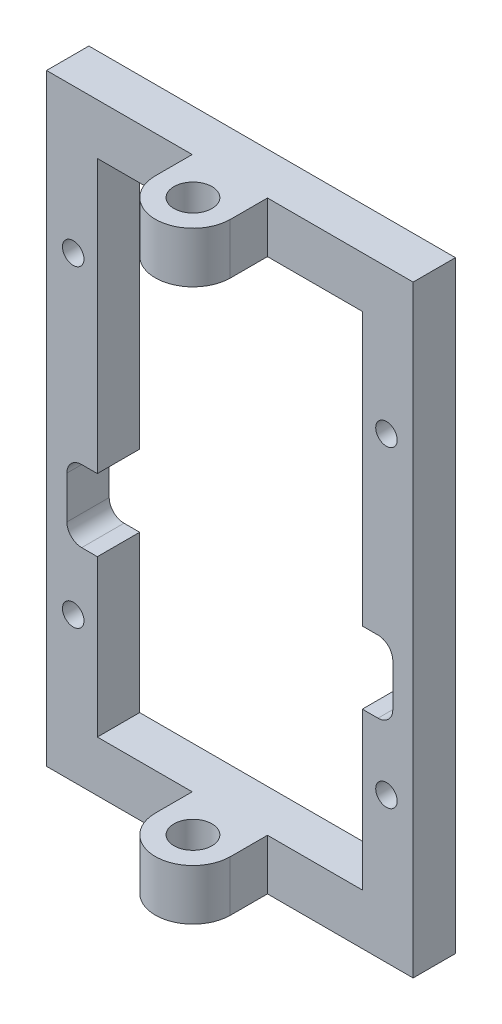
SolidWorks part; units mm, degrees
ref_plane "Front Plane" through (0, 0, 0) normal (0, 0, 1) x (1, 0, 0)
ref_plane "Top Plane" through (0, 0, 0) normal (0, 1, 0) x (1, 0, 0)
ref_plane "Right Plane" through (0, 0, 0) normal (1, 0, 0) x (0, 0, -1)
sketch "Sketch2" plane through (0, 0, 0) normal (0, 0, 1) x (1, 0, 0)
  line L1 (-21.65, 35.595) -> (21.65, 35.595)
  line L2 (-21.65, 35.595) -> (-21.65, -35.595)
  line L3 (-21.65, -35.595) -> (21.65, -35.595)
  line L4 (21.65, 35.595) -> (21.65, -35.595)
  line L5 (-15.65, 29.595) -> (15.65, 29.595)
  line L6 (-15.65, 29.595) -> (-15.65, -29.595)
  line L7 (-15.65, -29.595) -> (15.65, -29.595)
  line L8 (15.65, 29.595) -> (15.65, -29.595)
  dimension "D1" = 71.19
  dimension "D2" = 43.3
  dimension "D3" = 35.595
  dimension "D4" = 21.65
  dimension "D5" = 6
  dimension "D6" = 6
  dimension "D7" = 6
  dimension "D8" = 6
extrude "Boss-Extrude1" add sketch "Sketch2" along normal blind 5
sketch "Sketch3" plane through (0, 0, 5) normal (0, 0, 1) x (1, 0, 0)
  line L0 (0, 35.595) -> (0, -35.595)
  line L1 (21.65, 35.595) -> (-21.65, 35.595) construction
  line L2 (-21.65, -35.595) -> (21.65, -35.595) construction
  line L3 (15.65, 29.595) -> (-15.65, 29.595) construction
  line L4 (-4.445, 35.595) -> (4.445, 35.595)
  line L5 (-4.445, 35.595) -> (-4.445, 29.595)
  line L6 (-4.445, 29.595) -> (4.445, 29.595)
  line L7 (4.445, 35.595) -> (4.445, 29.595)
  line L8 (-15.65, -29.595) -> (15.65, -29.595) construction
  line L9 (-4.445, -29.595) -> (4.445, -29.595)
  line L10 (-4.445, -29.595) -> (-4.445, -35.595)
  line L11 (-4.445, -35.595) -> (4.445, -35.595)
  line L12 (4.445, -29.595) -> (4.445, -35.595)
  point P18 (4.445, -32.595)
  dimension "D1" = 8.89
  dimension "D2" = 4.445
  dimension "D3" = 8.89
extrude "Boss-Extrude2" add sketch "Sketch3" along normal blind 8.8 contours L4 L7 L6 L5 | L9 L12 L11 L10
sketch "Sketch5" plane through (0, 35.595, 0) normal (0, 1, 0) x (1, 0, 0)
  line L0 (4.445, -13.8) -> (4.445, -5) construction
  line L1 (-4.445, -13.8) -> (-4.445, -5) construction
  arc A0 (4.445, -9.4) -> (-4.445, -9.4) centre (0, -9.3548) cw
  circle A1 centre (0, -9.3548) radius 2.2479
  line M5 (-4.445, -5) -> (-4.445, -13.8)
  line M6 (-4.445, -13.8) -> (4.445, -13.8)
  line M7 (4.445, -13.8) -> (4.445, -5)
extrude "Cut-Extrude1" cut sketch "Sketch5" against normal through all and the other way through all contours A0 M6 M5 | A0 M7 M6 | A1
sketch "Sketch6" plane through (0, 0, 0) normal (0, 0, -1) x (-1, 0, 0)
  line L0 (-21.65, 35.595) -> (21.65, 35.595) construction
  line L1 (-21.65, -35.595) -> (-21.65, 35.595) construction
  line L2 (21.65, 35.595) -> (21.65, -35.595) construction
  line L3 (21.65, -35.595) -> (-21.65, -35.595) construction
  line L4 (-17.5, -2.5899) -> (-15.65, -2.5899)
  line L5 (-15.65, -29.595) -> (-15.65, 29.595) construction
  line L6 (-17.5, -11.0899) -> (-15.65, -11.0899)
  line L7 (-19.25, -4.3399) -> (-19.25, -9.3399)
  line L8 (17.5, -2.645) -> (15.65, -2.645)
  line L9 (15.65, 29.595) -> (15.65, -29.595) construction
  line L10 (19.25, -4.395) -> (19.25, -9.395)
  line L11 (17.5, -11.145) -> (15.65, -11.145)
  circle A0 centre (-18.5, 18.495) radius 1.27
  circle A1 centre (18.5, 18.495) radius 1.27
  circle A2 centre (18.5, -18.495) radius 1.27
  circle A3 centre (-18.5, -18.4399) radius 1.27
  circle A4 centre (-17.5, -9.3399) radius 1.75
  circle A5 centre (17.5, -9.395) radius 1.75
  circle A6 centre (-17.5, -4.3399) radius 1.75
  circle A7 centre (17.5, -4.395) radius 1.75
  line M5 (15.65, 29.595) -> (15.65, -29.595)
  line M7 (-15.65, -29.595) -> (-15.65, 29.595)
  dimension "D1" = 17.1
  dimension "D4" = 17.1
  dimension "D5" = 3.15
  dimension "D6" = 9.1
  dimension "D7" = 5
  dimension "D8" = 4.15
  dimension "D12" = 9.1
  dimension "D2" = 3.15
  dimension "D3" = 3.15
  dimension "D9" = 4.15
  dimension "D10" = 4.15
  dimension "D11" = 4.15
  dimension "D13" = 5
extrude "Cut-Extrude2" cut sketch "Sketch6" against normal blind 5 contours A6 L7 A4 L6 L4 M7 | A6 | A4 | A5 | A7 L8 L11 A5 L10 M5 | A7 | A0 | A1 | A2 | A3
